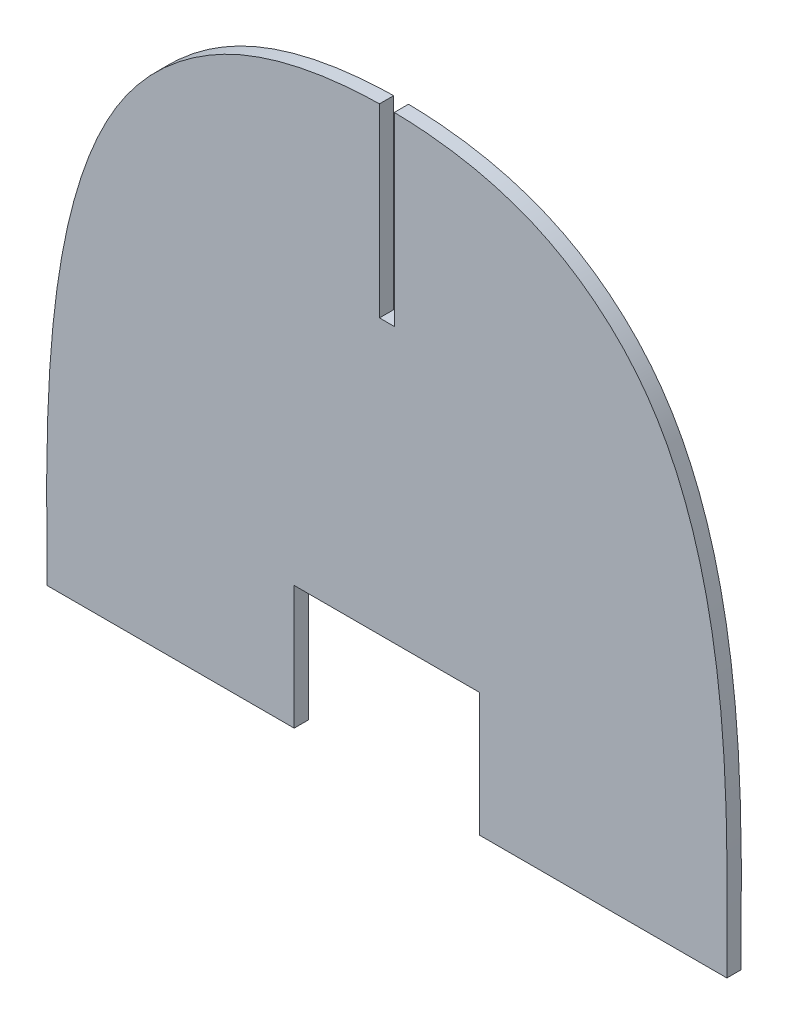
SolidWorks part; units mm, degrees
ref_plane "Front" through (0, 0, 0) normal (0, 0, 1) x (1, 0, 0)
ref_plane "Top" through (0, 0, 0) normal (0, 1, 0) x (1, 0, 0)
ref_plane "Right" through (0, 0, 0) normal (1, 0, 0) x (0, 0, -1)
sketch "Sketch1" plane through (0, 0, 0) normal (0, 0, 1) x (1, 0, 0)
  line L0 (0, 279.4) -> (67.5642, 279.4) construction
  line L1 (139.7, 39.6875) -> (139.7, 171.2154) construction
  spline S0 degree 3 poles (0, 279.4) (19.7788, 279.4) (60.7121, 273.8453) (104.0601, 240.0966) (142.8402, 163.9045) (139.7, 82.9966) (139.7, 39.6875) knots 0 0 0 0 0.194661 0.367202 0.497163 1 1 1 1
sketch "Sketch2" plane through (0, 0, 0) normal (0, 0, 1) x (1, 0, 0)
  line L0 (139.7, 39.6875) -> (0, 39.6875)
  line L1 (0, 39.6875) -> (0, 279.4)
  spline S0 degree 3 poles (3761.7043, 1629.083) (-619.3971, -156.7558) (-100.6638, 399.4849) (104.0601, 240.0966) (247.8687, -42.4471) (-281.2619, -724.6987) (2216.2566, 3457.0346) knots -1.850841 -1.850841 -1.850841 -1.850841 0.194661 0.367202 0.497163 3.181105 3.181105 3.181105 3.181105 only from (0, 279.4) to (139.7, 39.6875) construction
  spline S1 degree 3 poles (0, 279.4) (19.7788, 279.4) (60.7121, 273.8453) (104.0601, 240.0966) (142.8402, 163.9045) (139.7, 82.9966) (139.7, 39.6875) knots 0 0 0 0 0.194661 0.367202 0.497163 1 1 1 1
extrude "Boss-Extrude1" add sketch "Sketch2" along normal blind 5.842
sketch "Sketch3" plane through (0, 0, 5.842) normal (0, 0, 1) x (1, 0, 0)
  line L1 (0, 39.6875) -> (38.1, 39.6875)
  line L2 (0, 39.6875) -> (0, 90.4875)
  line L3 (0, 90.4875) -> (38.1, 90.4875)
  line L4 (38.1, 39.6875) -> (38.1, 90.4875)
  line L5 (0, 279.4) -> (3.048, 279.4)
  line L6 (0, 279.4) -> (0, 203.2)
  line L7 (0, 203.2) -> (3.048, 203.2)
  line L8 (3.048, 279.4) -> (3.048, 203.2)
  dimension "D1" = 38.1
  dimension "D2" = 50.8
  dimension "D3" = 76.2
  dimension "D4" = 3.048
extrude "Cut-Extrude1" cut sketch "Sketch3" against normal through all
mirror "Mirror1" about plane through (0, 0, 0) normal (1, 0, 0) of bodies 102
